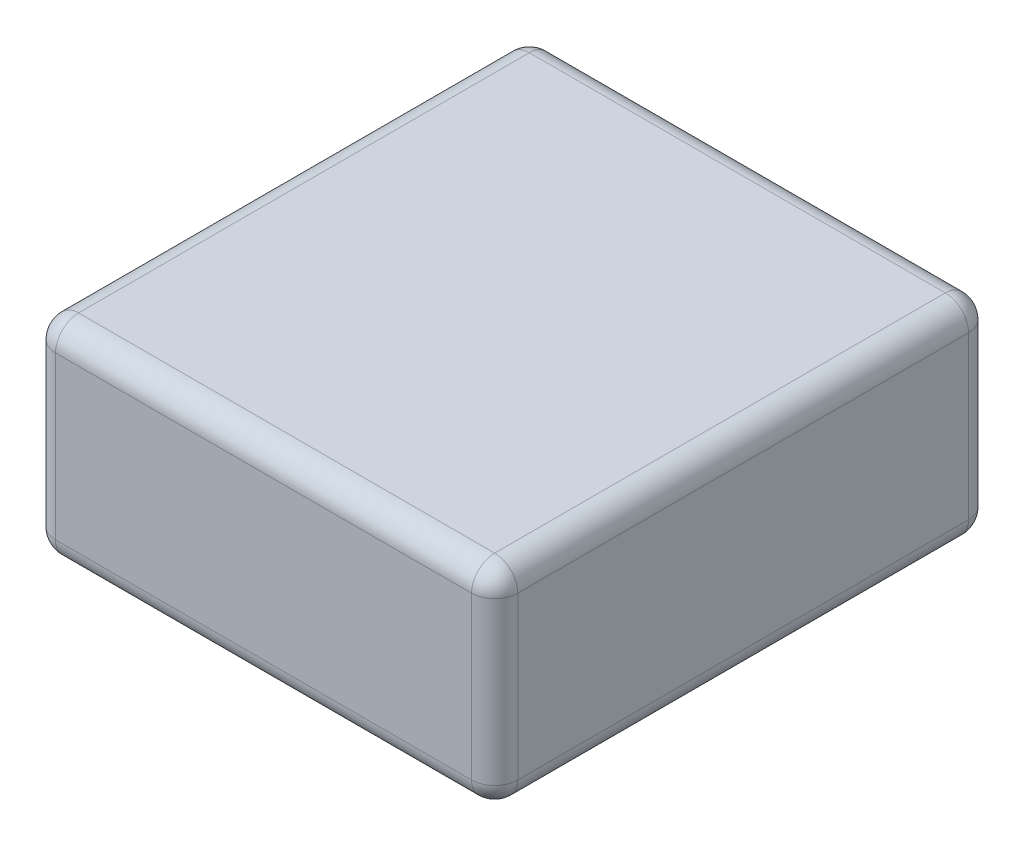
SolidWorks part; units mm, degrees
ref_plane "Plan de face" through (0, 0, 0) normal (0, 0, 1) x (1, 0, 0)
ref_plane "Plan de dessus" through (0, 0, 0) normal (0, 1, 0) x (1, 0, 0)
ref_plane "Plan de droite" through (0, 0, 0) normal (1, 0, 0) x (0, 0, -1)
sketch "Esquisse1" plane through (0, 0, 0) normal (0, 0, 1) x (1, 0, 0)
  line L1 (-100, 45) -> (100, 45)
  line L2 (-100, 45) -> (-100, -45)
  line L3 (-100, -45) -> (100, -45)
  line L4 (100, 45) -> (100, -45)
  line L5 (-100, 45) -> (100, -45) construction
  line L6 (-100, -45) -> (100, 45) construction
  point P0 (0, 0)
  dimension "D1" = 90
  dimension "D2" = 200
extrude "Boss.-Extru.1" add sketch "Esquisse1" against normal blind 215
fillet "Congé1" radius 10 12 edges at (0, -45, -215) (100, 0, -215) (100, -45, -107.5) (-100, -45, -107.5) (-100, 0, -215) (0, -45, 0) (-100, 0, 0) (100, 0, 0) (-100, 45, -107.5) (0, 45, -215) (100, 45, -107.5) (0, 45, 0)
